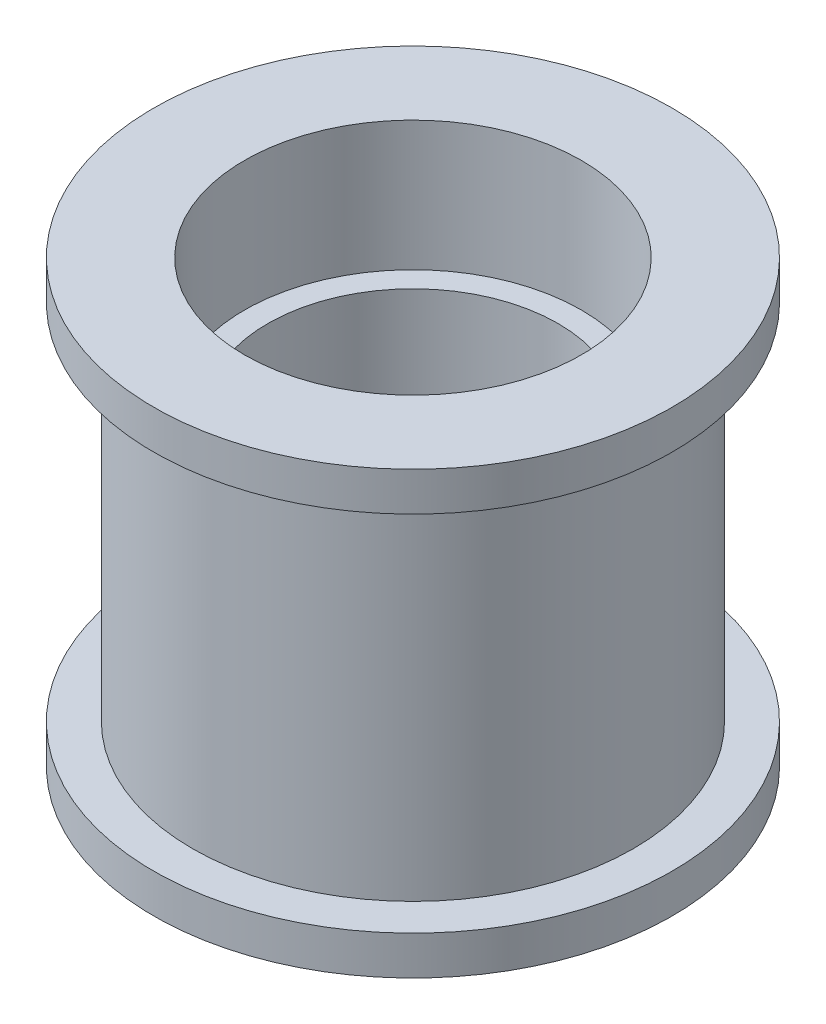
SolidWorks part; units mm, degrees
ref_plane "Спереди" through (0, 0, 0) normal (0, 0, 1) x (1, 0, 0)
ref_plane "Сверху" through (0, 0, 0) normal (0, 1, 0) x (1, 0, 0)
ref_plane "Справа" through (0, 0, 0) normal (1, 0, 0) x (0, 0, -1)
sketch "Эскиз1" plane through (0, 0, 0) normal (0, 0, 1) x (1, 0, 0)
  line L0 (0, 0) -> (0, 57.138) construction
  line L1 (0, 0) -> (66.9746, 0) construction
  line L2 (5.6, -3.5) -> (5.6, 3.5)
  line L3 (5.6, 3.5) -> (6.5, 3.5)
  line L4 (6.5, 3.5) -> (6.5, 8.5)
  line L5 (6.5, 8.5) -> (10, 8.5)
  line L6 (10, 8.5) -> (10, 7)
  line L7 (10, 7) -> (8.5, 7)
  line L8 (8.5, 7) -> (8.5, -7)
  line L9 (10, -7) -> (8.5, -7)
  line L10 (10, -8.5) -> (10, -7)
  line L11 (6.5, -8.5) -> (10, -8.5)
  line L12 (6.5, -3.5) -> (6.5, -8.5)
  line L13 (5.6, -3.5) -> (6.5, -3.5)
  point P13 (8.5, 0)
  point P18 (5.6, 0)
  dimension "D1" = 11.2
  dimension "D2" = 5
  dimension "D3" = 1.5
  dimension "D4" = 1.5
  dimension "D5" = 14
  dimension "D6" = 17
  dimension "D7" = 13
revolve "Повернуть1" add sketch "Эскиз1" angle 360 about L0
